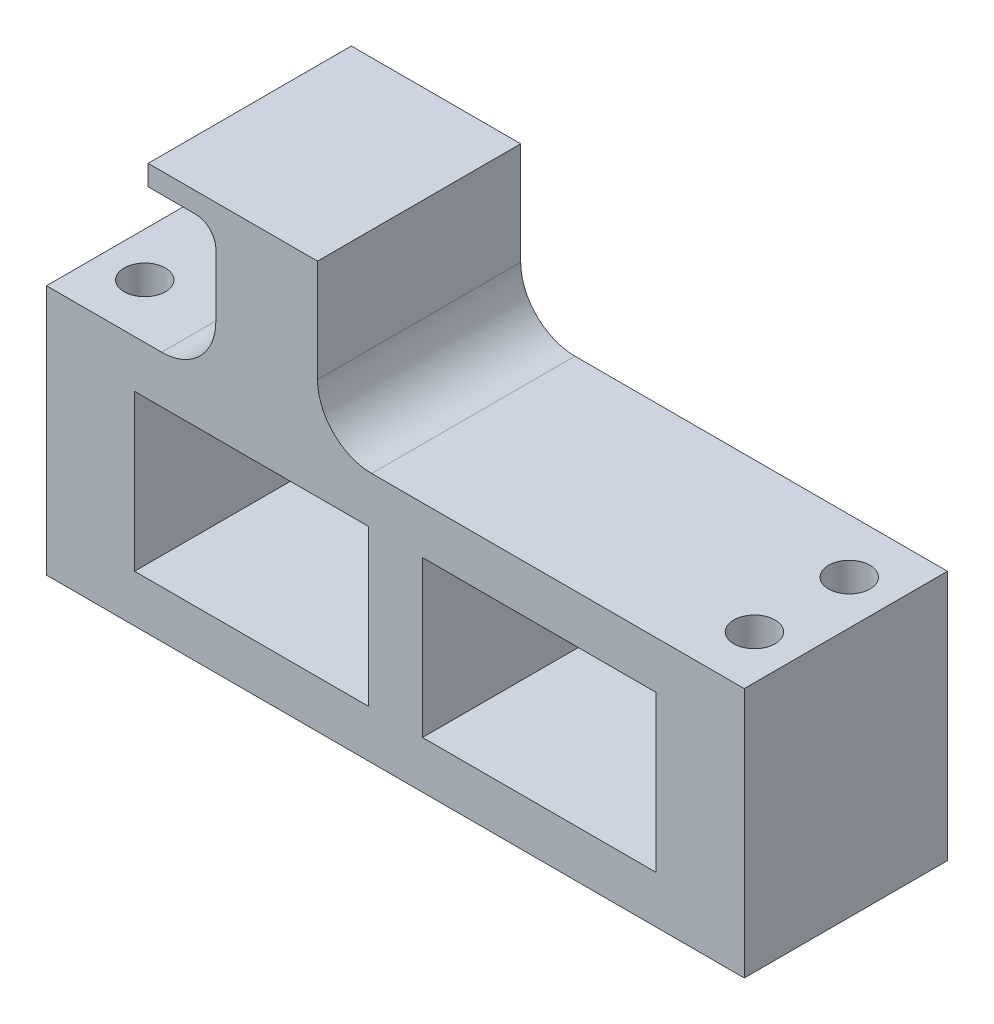
SolidWorks part; units mm, degrees
ref_plane "Front Plane" through (0, 0, 0) normal (0, 0, 1) x (1, 0, 0)
ref_plane "Top Plane" through (0, 0, 0) normal (0, 1, 0) x (1, 0, 0)
ref_plane "Right Plane" through (0, 0, 0) normal (1, 0, 0) x (0, 0, -1)
sketch "Sketch1" plane through (0, 0, 0) normal (0, 1, 0) x (1, 0, 0)
  line L1 (0, 0) -> (103, 0)
  line L2 (0, 0) -> (0, 30)
  line L3 (0, 30) -> (103, 30)
  line L4 (103, 0) -> (103, 30)
  dimension "D1" = 103
  dimension "D2" = 30
extrude "Boss-Extrude1" add sketch "Sketch1" along normal blind 7 contours L1 L4 L3 L2
sketch "Sketch2" plane through (0, 7, 0) normal (0, 1, 0) x (1, 0, 0)
  line L0 (0, 30) -> (103, 30) construction
  line L1 (0, 0) -> (13, 0)
  line L2 (0, 0) -> (0, 30)
  line L3 (0, 30) -> (13, 30)
  line L4 (13, 0) -> (13, 30)
  line L5 (51.5, 0) -> (51.5, 30) construction
  line L6 (0, 0) -> (103, 0) construction
  line L7 (55.5, 30) -> (55.5, 0)
  line L8 (55.5, 30) -> (47.5, 30)
  line L9 (51.5, 30) -> (51.5, 0)
  line L10 (55.5, 0) -> (47.5, 0)
  line L11 (47.5, 30) -> (47.5, 0)
  line L12 (103, 30) -> (90, 30)
  line L13 (103, 0) -> (90, 0)
  line L14 (103, 0) -> (103, 30)
  line L15 (90, 0) -> (90, 30)
  line M9 (0, 30) -> (0, 0)
  line M10 (0, 0) -> (103, 0)
  line M11 (103, 0) -> (103, 30)
  line M12 (103, 30) -> (0, 30)
  dimension "D1" = 13
  dimension "D2" = 4
extrude "Boss-Extrude2" add sketch "Sketch2" along normal blind 23 contours L4 M10 M12 M9 | L8 L11 L9 M10 | L9 L7 M12 M10 | L15 M10 M11 M12
sketch "Sketch3" plane through (0, 30, 0) normal (0, 1, 0) x (1, 0, 0)
  line L1 (0, 0) -> (103, 0)
  line L2 (0, 0) -> (0, 30)
  line L3 (0, 30) -> (103, 30)
  line L4 (103, 0) -> (103, 30)
extrude "Boss-Extrude3" add sketch "Sketch3" along normal blind 7
sketch "Sketch4" plane through (0, 37, 0) normal (0, 1, 0) x (1, 0, 0)
  line L0 (0, 30) -> (0, 0) construction
  line L1 (25, 0) -> (40, 0)
  line L2 (25, 0) -> (25, 30)
  line L3 (25, 30) -> (40, 30)
  line L4 (40, 0) -> (40, 30)
  line L5 (0, 0) -> (103, 0) construction
  line L6 (103, 30) -> (0, 30) construction
  dimension "D1" = 25
  dimension "D2" = 15
extrude "Boss-Extrude4" add sketch "Sketch4" along normal blind 20.15
sketch "Sketch5" plane through (0, 57.15, 0) normal (0, 1, 0) x (1, 0, 0)
  line L0 (40, 0) -> (40, 30) construction
  line L1 (15, 30) -> (40, 30)
  line L2 (15, 30) -> (15, 0)
  line L3 (15, 0) -> (40, 0)
  line L4 (40, 30) -> (40, 0)
  line L5 (25, 0) -> (40, 0) construction
  line L6 (40, 30) -> (25, 30) construction
  dimension "D2" = 25
extrude "Boss-Extrude5" add sketch "Sketch5" along normal blind 3
fillet "Fillet2" radius 3 1 edges at (25, 57.15, -15)
fillet "Fillet3" radius 8 2 edges at (40, 37, -15) (25, 37, -15)
sketch "Sketch6" plane through (0, 0, 0) normal (0, -1, 0) x (1, 0, 0)
  line L0 (0, 0) -> (0, -30) construction
  line L1 (0, -30) -> (103, -30) construction
  line L2 (0, -15) -> (103, -15) construction
  line L3 (103, 0) -> (103, -30) construction
  line L4 (51.5, -30) -> (51.5, 0) construction
  line L5 (0, 0) -> (103, 0) construction
  circle A0 centre (6.5, -22) radius 3.05
  circle A1 centre (6.5, -8) radius 3.05
  circle A2 centre (96.5, -8) radius 3.05
  circle A3 centre (96.5, -22) radius 3.05
  dimension "D1" = 6.1
  dimension "D2" = 6.5
  dimension "D3" = 8
extrude "Cut-Extrude1" cut sketch "Sketch6" against normal blind 40
